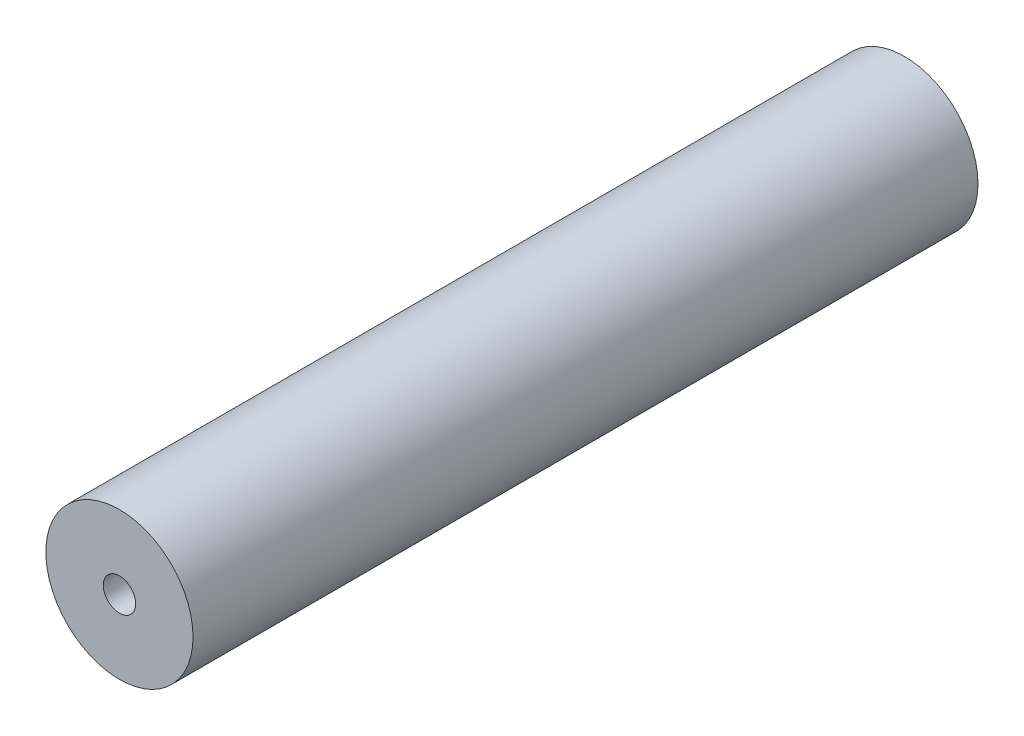
SolidWorks part; units mm, degrees
material "5052-H34"
ref_plane "正面" through (0, 0, 0) normal (0, 0, 1) x (1, 0, 0)
ref_plane "平面" through (0, 0, 0) normal (0, 1, 0) x (1, 0, 0)
ref_plane "右側面" through (0, 0, 0) normal (1, 0, 0) x (0, 0, -1)
sketch "ｽｹｯﾁ1" plane through (0, 0, 0) normal (0, 0, 1) x (1, 0, 0)
  circle A0 centre (0, 0) radius 7.5
  dimension "D1" = 15
extrude "ﾎﾞｽ - 押し出し1" add sketch "ｽｹｯﾁ1" along normal blind 80
sketch "ｽｹｯﾁ2" plane through (0, 0, 80) normal (0, 0, 1) x (1, 0, 0)
  circle A0 centre (0, 0) radius 1.65
  dimension "D1" = 3.3
extrude "ｶｯﾄ - 押し出し1" cut sketch "ｽｹｯﾁ2" against normal blind 10
ref_plane "平面1" through (0, 0, 40) normal (0, 0, 1) x (1, 0, 0)
mirror "ﾐﾗｰ1" about plane through (0, 0, 40) normal (0, 0, 1) of "ｶｯﾄ - 押し出し1"
